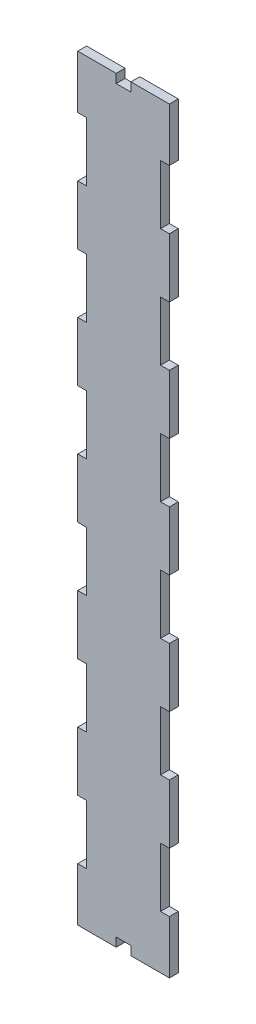
SolidWorks part; units mm, degrees
ref_plane "Front Plane" through (0, 0, 0) normal (0, 0, 1) x (1, 0, 0)
ref_plane "Top Plane" through (0, 0, 0) normal (0, 1, 0) x (1, 0, 0)
ref_plane "Right Plane" through (0, 0, 0) normal (1, 0, 0) x (0, 0, -1)
sketch "Эскиз2" plane through (0, 0, 0) normal (0, 0, 1) x (1, 0, 0)
  line L0 (-118.1292, 271.6721) -> (-110.4161, 271.6721)
  line L1 (-110.4161, 271.6721) -> (-110.4161, 276.0661)
  line L2 (-110.4161, 276.0661) -> (-86.722, 276.0661)
  line L3 (-86.722, 276.0661) -> (-86.722, 271.6721)
  line L4 (-86.722, 271.6721) -> (-64.5567, 271.6721)
  line L5 (-64.5567, 271.6721) -> (-64.5567, 276.0661)
  line L6 (-64.5567, 276.0661) -> (-40.8626, 276.0661)
  line L7 (-40.8626, 276.0661) -> (-40.8626, 271.6721)
  line L8 (-40.8626, 271.6721) -> (-10.2897, 271.6721)
  line L9 (-10.2897, 271.6721) -> (-10.2897, 248.237)
  line L10 (-10.2897, 248.237) -> (-4.5573, 248.237)
  line L11 (-4.5573, 248.237) -> (-4.5573, 230.0748)
  line L12 (-4.5573, 230.0748) -> (-10.2897, 230.0748)
  line L13 (-10.2897, 230.0748) -> (-10.2897, 213.0843)
  line L14 (-10.2897, 213.0843) -> (-4.5573, 213.0843)
  line L15 (-4.5573, 213.0843) -> (-4.5573, 194.9221)
  line L16 (-4.5573, 194.9221) -> (-10.2897, 194.9221)
  line L17 (-10.2897, 194.9221) -> (-10.2897, 177.9317)
  line L18 (-10.2897, 177.9317) -> (-4.5573, 177.9317)
  line L19 (-4.5573, 177.9317) -> (-4.5573, 159.7695)
  line L20 (-4.5573, 159.7695) -> (-10.2897, 159.7695)
  line L21 (-10.2897, 159.7695) -> (-10.2897, 142.7791)
  line L22 (-10.2897, 142.7791) -> (-4.5573, 142.7791)
  line L23 (-4.5573, 142.7791) -> (-4.5573, 124.6169)
  line L24 (-4.5573, 124.6169) -> (-10.2897, 124.6169)
  line L25 (-10.2897, 124.6169) -> (-10.2897, 107.6264)
  line L26 (-10.2897, 107.6264) -> (-4.5573, 107.6264)
  line L27 (-4.5573, 107.6264) -> (-4.5573, 89.4642)
  line L28 (-4.5573, 89.4642) -> (-10.2897, 89.4642)
  line L29 (-10.2897, 89.4642) -> (-10.2897, 72.4738)
  line L30 (-10.2897, 72.4738) -> (-4.5573, 72.4738)
  line L31 (-4.5573, 72.4738) -> (-4.5573, 54.3116)
  line L32 (-4.5573, 54.3116) -> (-10.2897, 54.3116)
  line L33 (-10.2897, 21.59) -> (-41.4508, 21.59)
  line L34 (-41.4508, 21.59) -> (-41.4508, 17.1959)
  line L35 (-41.4508, 17.1959) -> (-65.1449, 17.1959)
  line L36 (-65.1449, 17.1959) -> (-65.1449, 21.59)
  line L37 (-65.1449, 21.59) -> (-87.3102, 21.59)
  line L38 (-87.3102, 21.59) -> (-87.3102, 17.1959)
  line L39 (-87.3102, 17.1959) -> (-111.0043, 17.1959)
  line L40 (-111.0043, 17.1959) -> (-111.0043, 21.59)
  line L41 (-111.0043, 21.59) -> (-118.7174, 21.59)
  line L42 (-118.7174, 21.59) -> (-133.1696, 21.59)
  line L43 (-133.1696, 21.59) -> (-133.1696, 17.1959)
  line L44 (-133.1696, 17.1959) -> (-156.8637, 17.1959)
  line L45 (-156.8637, 17.1959) -> (-156.8637, 21.59)
  line L46 (-156.8637, 21.59) -> (-179.029, 21.59)
  line L47 (-179.029, 21.59) -> (-179.029, 17.1959)
  line L48 (-179.029, 17.1959) -> (-202.7231, 17.1959)
  line L49 (-202.7231, 17.1959) -> (-202.7231, 21.59)
  line L50 (-202.7231, 21.59) -> (-224.8885, 21.59)
  line L51 (-224.8885, 21.59) -> (-224.8885, 17.1959)
  line L52 (-224.8885, 17.1959) -> (-248.5825, 17.1959)
  line L53 (-248.5825, 17.1959) -> (-248.5825, 21.59)
  line L54 (-248.5825, 21.59) -> (-270.7479, 21.59)
  line L55 (-270.7479, 21.59) -> (-270.7479, 17.1959)
  line L56 (-270.7479, 17.1959) -> (-294.4419, 17.1959)
  line L57 (-294.4419, 17.1959) -> (-294.4419, 21.59)
  line L58 (-294.4419, 21.59) -> (-316.6073, 21.59)
  line L59 (-316.6073, 21.59) -> (-316.6073, 17.1959)
  line L60 (-316.6073, 17.1959) -> (-340.3013, 17.1959)
  line L61 (-340.3013, 17.1959) -> (-340.3013, 21.59)
  line L62 (-340.3013, 21.59) -> (-370.286, 21.59)
  line L63 (-370.286, 21.59) -> (-370.286, 54.3116)
  line L64 (-370.286, 54.3116) -> (-376.0185, 54.3116)
  line L65 (-376.0185, 54.3116) -> (-376.0185, 72.4738)
  line L66 (-376.0185, 72.4738) -> (-370.286, 72.4738)
  line L67 (-370.286, 72.4738) -> (-370.286, 89.4642)
  line L68 (-370.286, 89.4642) -> (-376.0185, 89.4642)
  line L69 (-376.0185, 89.4642) -> (-376.0185, 107.6264)
  line L70 (-376.0185, 107.6264) -> (-370.286, 107.6264)
  line L71 (-370.286, 107.6264) -> (-370.286, 124.6169)
  line L72 (-370.286, 124.6169) -> (-376.0185, 124.6169)
  line L73 (-376.0185, 124.6169) -> (-376.0185, 142.7791)
  line L74 (-376.0185, 142.7791) -> (-370.286, 142.7791)
  line L75 (-370.286, 142.7791) -> (-370.286, 159.7695)
  line L76 (-370.286, 159.7695) -> (-376.0185, 159.7695)
  line L77 (-376.0185, 159.7695) -> (-376.0185, 177.9317)
  line L78 (-376.0185, 177.9317) -> (-370.286, 177.9317)
  line L79 (-370.286, 177.9317) -> (-370.286, 194.9221)
  line L80 (-370.286, 194.9221) -> (-376.0185, 194.9221)
  line L81 (-376.0185, 194.9221) -> (-376.0185, 213.0843)
  line L82 (-376.0185, 213.0843) -> (-370.286, 213.0843)
  line L83 (-370.286, 213.0843) -> (-370.286, 230.0748)
  line L84 (-370.286, 230.0748) -> (-376.0185, 230.0748)
  line L85 (-376.0185, 230.0748) -> (-376.0185, 248.237)
  line L86 (-376.0185, 248.237) -> (-370.286, 248.237)
  line L87 (-370.286, 248.237) -> (-370.286, 271.6721)
  line L88 (-370.286, 271.6721) -> (-339.7131, 271.6721)
  line L89 (-339.7131, 271.6721) -> (-339.7131, 276.0661)
  line L90 (-339.7131, 276.0661) -> (-316.0191, 276.0661)
  line L91 (-316.0191, 276.0661) -> (-316.0191, 271.6721)
  line L92 (-316.0191, 271.6721) -> (-293.8537, 271.6721)
  line L93 (-293.8537, 271.6721) -> (-293.8537, 276.0661)
  line L94 (-293.8537, 276.0661) -> (-270.1597, 276.0661)
  line L95 (-270.1597, 276.0661) -> (-270.1597, 271.6721)
  line L96 (-270.1597, 271.6721) -> (-247.9943, 271.6721)
  line L97 (-247.9943, 271.6721) -> (-247.9943, 276.0661)
  line L98 (-247.9943, 276.0661) -> (-224.3003, 276.0661)
  line L99 (-224.3003, 276.0661) -> (-224.3003, 271.6721)
  line L100 (-224.3003, 271.6721) -> (-202.1349, 271.6721)
  line L101 (-202.1349, 271.6721) -> (-202.1349, 276.0661)
  line L102 (-202.1349, 276.0661) -> (-178.4408, 276.0661)
  line L103 (-178.4408, 276.0661) -> (-178.4408, 271.6721)
  line L104 (-178.4408, 271.6721) -> (-156.2755, 271.6721)
  line L105 (-156.2755, 271.6721) -> (-156.2755, 276.0661)
  line L106 (-156.2755, 276.0661) -> (-132.5814, 276.0661)
  line L107 (-132.5814, 276.0661) -> (-132.5814, 271.6721)
  line L108 (-132.5814, 271.6721) -> (-118.1292, 271.6721)
  line L109 (-373.2759, 10.3396) -> (-342.8312, 10.3396)
  line L110 (-342.8312, 10.3396) -> (-342.8312, 6.0284)
  line L111 (-342.8312, 6.0284) -> (-318.4281, 6.0284)
  line L112 (-318.4281, 6.0284) -> (-318.4281, 10.3396)
  line L113 (-318.4281, 10.3396) -> (-296.972, 10.3396)
  line L114 (-296.972, 10.3396) -> (-296.972, 6.0284)
  line L115 (-296.972, 6.0284) -> (-272.5865, 6.0284)
  line L116 (-272.5865, 6.0284) -> (-272.5865, 10.3396)
  line L117 (-272.5865, 10.3396) -> (-251.1875, 10.3396)
  line L118 (-251.1875, 10.3396) -> (-251.1875, 6.0284)
  line L119 (-251.1875, 6.0284) -> (-226.6927, 6.0284)
  line L120 (-226.6927, 6.0284) -> (-226.6927, 10.3396)
  line L121 (-226.6927, 10.3396) -> (-205.259, 10.3396)
  line L122 (-205.259, 10.3396) -> (-205.259, 6.0284)
  line L123 (-205.259, 6.0284) -> (-180.8925, 6.0284)
  line L124 (-180.8925, 6.0284) -> (-180.8925, 10.3396)
  line L125 (-180.8925, 10.3396) -> (-159.5195, 10.3396)
  line L126 (-159.5195, 10.3396) -> (-159.5195, 6.0284)
  line L127 (-159.5195, 6.0284) -> (-135.0267, 6.0284)
  line L128 (-135.0267, 6.0284) -> (-135.0267, 10.3396)
  line L129 (-135.0267, 10.3396) -> (-113.5788, 10.3396)
  line L130 (-113.5788, 10.3396) -> (-113.5788, 6.0284)
  line L131 (-113.5788, 6.0284) -> (-89.2114, 6.0284)
  line L132 (-89.2114, 6.0284) -> (-89.2114, 10.3396)
  line L133 (-89.2114, 10.3396) -> (-67.739, 10.3396)
  line L134 (-67.739, 10.3396) -> (-67.739, 6.0284)
  line L135 (-67.739, 6.0284) -> (-43.1804, 6.0284)
  line L136 (-43.1804, 6.0284) -> (-43.1804, 10.3396)
  line L137 (-43.1804, 10.3396) -> (-12.8557, 10.3396)
  line L138 (-12.8557, 10.3396) -> (-12.8557, -1.3472)
  line L139 (-12.8557, -1.3472) -> (-4.8129, -1.3472)
  line L140 (-4.8129, -1.3472) -> (-4.8194, -8.2165)
  line L141 (-4.8194, -8.2165) -> (-12.8557, -8.2165)
  line L142 (-12.8557, -8.2165) -> (-12.8557, -21.1423)
  line L143 (-12.8557, -21.1423) -> (-43.1804, -21.1423)
  line L144 (-43.1804, -21.1423) -> (-43.1804, -17.4156)
  line L145 (-43.1804, -17.4156) -> (-67.739, -17.4156)
  line L146 (-67.739, -17.4156) -> (-67.739, -21.1423)
  line L147 (-67.739, -21.1423) -> (-89.2114, -21.1423)
  line L148 (-89.2114, -21.1423) -> (-89.2114, -17.4156)
  line L149 (-89.2114, -17.4156) -> (-113.5788, -17.4156)
  line L150 (-113.5788, -17.4156) -> (-113.5788, -21.1423)
  line L151 (-113.5788, -21.1423) -> (-135.0267, -21.1423)
  line L152 (-135.0267, -21.1423) -> (-135.0267, -17.4156)
  line L153 (-135.0267, -17.4156) -> (-159.5195, -17.4156)
  line L154 (-159.5195, -17.4156) -> (-159.5195, -21.1423)
  line L155 (-159.5195, -21.1423) -> (-180.8925, -21.1423)
  line L156 (-180.8925, -21.1423) -> (-180.8931, -17.4156)
  line L157 (-180.8931, -17.4156) -> (-205.259, -17.4156)
  line L158 (-205.259, -17.4156) -> (-205.259, -21.1423)
  line L159 (-205.259, -21.1423) -> (-226.6927, -21.1423)
  line L160 (-226.6927, -21.1423) -> (-226.6927, -17.4156)
  line L161 (-226.6927, -17.4156) -> (-251.1875, -17.4156)
  line L162 (-251.1875, -17.4156) -> (-251.1875, -21.1423)
  line L163 (-251.1875, -21.1423) -> (-272.5865, -21.1423)
  line L164 (-272.5865, -21.1423) -> (-272.5865, -17.4156)
  line L165 (-272.5865, -17.4156) -> (-296.972, -17.4156)
  line L166 (-296.972, -17.4156) -> (-296.972, -21.1423)
  line L167 (-296.972, -21.1423) -> (-318.4281, -21.1423)
  line L168 (-318.4281, -21.1423) -> (-318.4281, -17.4156)
  line L169 (-318.4281, -17.4156) -> (-342.8312, -17.4156)
  line L170 (-342.8312, -17.4156) -> (-342.8312, -21.1423)
  line L171 (-342.8312, -21.1423) -> (-373.2759, -21.1423)
  line L172 (-373.2759, -21.1423) -> (-373.2759, -8.4164)
  line L173 (-373.2759, -8.4164) -> (-379.9791, -8.4164)
  line L174 (-379.9791, -8.4164) -> (-379.9791, -1.5471)
  line L175 (-379.9791, -1.5471) -> (-373.2759, -1.5471)
  line L176 (-373.2759, -1.5471) -> (-373.2759, 10.3396)
  line L177 (-309.7012, -8.7624) -> (-309.7012, -1.506)
  line L178 (-309.7012, -1.506) -> (-306.8626, -1.506)
  line L179 (-306.8626, -1.506) -> (-306.8626, -8.7624)
  line L180 (-306.8626, -8.7624) -> (-309.7012, -8.7624)
  line L181 (-339.711, -8.7225) -> (-339.711, -1.4885)
  line L182 (-339.711, -1.4885) -> (-336.8724, -1.4885)
  line L183 (-336.8724, -1.4885) -> (-336.8724, -8.7225)
  line L184 (-336.8724, -8.7225) -> (-339.711, -8.7225)
  line L185 (-279.6954, -8.7125) -> (-279.6954, -1.4785)
  line L186 (-279.6954, -1.4785) -> (-276.8568, -1.4785)
  line L187 (-276.8568, -1.4785) -> (-276.8568, -8.7125)
  line L188 (-276.8568, -8.7125) -> (-279.6954, -8.7125)
  line L189 (-249.6976, -8.7086) -> (-249.6976, -1.496)
  line L190 (-249.6976, -1.496) -> (-246.859, -1.496)
  line L191 (-246.859, -1.496) -> (-246.859, -8.7086)
  line L192 (-246.859, -8.7086) -> (-249.6976, -8.7086)
  line L193 (-189.6776, -8.5964) -> (-189.6776, -1.4885)
  line L194 (-189.6776, -1.4885) -> (-186.839, -1.4885)
  line L195 (-186.839, -1.4885) -> (-186.839, -8.5964)
  line L196 (-186.839, -8.5964) -> (-189.6776, -8.5964)
  line L197 (-216.8557, -1.4884) -> (-216.8557, -5.6266)
  line L198 (-216.8557, -5.6266) -> (-216.8557, -8.6615)
  line L199 (-216.8557, -8.6615) -> (-219.6943, -8.6615)
  line L200 (-219.6943, -8.6615) -> (-219.6943, -1.4884)
  line L201 (-219.6943, -1.4884) -> (-216.8557, -1.4884)
  line L202 (-159.6718, -8.4591) -> (-159.6718, -1.4885)
  line L203 (-159.6718, -1.4885) -> (-156.8332, -1.4885)
  line L204 (-156.8332, -1.4885) -> (-156.8332, -8.4591)
  line L205 (-156.8332, -8.4591) -> (-159.6718, -8.4591)
  line L206 (-126.0755, -8.4753) -> (-126.0755, -1.4794)
  line L207 (-126.0755, -1.4794) -> (-123.2266, -1.4794)
  line L208 (-123.2266, -1.4794) -> (-123.2266, -8.4753)
  line L209 (-123.2266, -8.4753) -> (-126.0755, -8.4753)
  line L210 (32.0426, 264.3465) -> (32.0426, 233.4466)
  line L211 (32.0426, 233.4466) -> (26.1557, 233.4466)
  line L212 (26.1557, 233.4466) -> (26.1557, 214.8844)
  line L213 (26.1557, 214.8844) -> (32.0426, 214.8844)
  line L214 (32.0426, 214.8844) -> (32.0426, 198.2939)
  line L215 (32.0426, 198.2939) -> (26.1557, 198.2939)
  line L216 (26.1557, 198.2939) -> (26.1557, 179.5405)
  line L217 (26.1557, 179.5405) -> (32.0426, 179.5405)
  line L218 (32.0426, 179.5405) -> (32.0426, 163.1413)
  line L219 (32.0426, 163.1413) -> (26.1557, 163.1413)
  line L220 (26.1557, 163.1413) -> (26.1557, 144.7791)
  line L221 (26.1557, 144.7791) -> (32.0426, 144.7791)
  line L222 (32.0426, 144.7791) -> (32.0426, 127.9887)
  line L223 (32.0426, 127.9887) -> (26.1557, 127.9887)
  line L224 (26.1557, 127.9887) -> (26.1557, 109.4265)
  line L225 (26.1557, 109.4265) -> (32.0426, 109.4265)
  line L226 (32.0426, 109.4265) -> (32.0426, 92.836)
  line L227 (32.0426, 92.836) -> (26.1557, 92.836)
  line L228 (26.1557, 92.836) -> (26.1557, 74.4738)
  line L229 (26.1557, 74.4738) -> (32.0426, 74.4738)
  line L230 (32.0426, 74.4738) -> (32.0426, 57.4834)
  line L231 (32.0426, 57.4834) -> (26.1557, 57.4834)
  line L232 (26.1557, 57.4834) -> (26.1557, 39.3212)
  line L233 (26.1557, 39.3212) -> (32.0426, 39.3212)
  line L234 (32.0426, 39.3212) -> (32.0426, 29.9952)
  line L235 (32.0426, 29.9952) -> (32.0426, -0.6964)
  line L236 (32.0426, -0.6964) -> (20.0028, -0.6964)
  line L237 (20.0028, -0.6964) -> (20.0028, 6.7202)
  line L238 (20.0028, 6.7202) -> (12.704, 6.7202)
  line L239 (12.704, 6.7202) -> (12.704, -0.6964)
  line L240 (12.704, -0.6964) -> (-0.0144, -0.6964)
  line L241 (-0.0144, 39.3212) -> (6.3507, 39.3212)
  line L242 (6.3507, 39.3212) -> (6.3507, 57.4834)
  line L243 (6.3507, 57.4834) -> (-0.0144, 57.4834)
  line L244 (-0.0144, 57.4834) -> (-0.0144, 74.4738)
  line L245 (-0.0144, 74.4738) -> (6.3507, 74.4738)
  line L246 (6.3507, 74.4738) -> (6.3507, 92.836)
  line L247 (6.3507, 92.836) -> (-0.0144, 92.836)
  line L248 (-0.0144, 92.836) -> (-0.0144, 109.4265)
  line L249 (-0.0144, 109.4265) -> (6.3507, 109.4265)
  line L250 (6.3507, 109.4265) -> (6.3507, 127.9887)
  line L251 (6.3507, 127.9887) -> (-0.0144, 127.9887)
  line L252 (-0.0144, 127.9887) -> (-0.0144, 144.7791)
  line L253 (-0.0144, 144.7791) -> (6.3507, 144.7791)
  line L254 (6.3507, 144.7791) -> (6.3507, 163.1413)
  line L255 (6.3507, 163.1413) -> (-0.0144, 163.1413)
  line L256 (-0.0144, 163.1413) -> (-0.0144, 179.5405)
  line L257 (-0.0144, 179.5405) -> (6.3507, 179.5405)
  line L258 (6.3507, 179.5405) -> (6.3507, 198.2939)
  line L259 (6.3507, 198.2939) -> (-0.0144, 198.2939)
  line L260 (-0.0144, 198.2939) -> (-0.0144, 214.8844)
  line L261 (-0.0144, 214.8844) -> (6.3507, 214.8844)
  line L262 (6.3507, 214.8844) -> (6.3507, 233.4466)
  line L263 (6.3507, 233.4466) -> (-0.0144, 233.4466)
  line L264 (-0.0144, 233.4466) -> (-0.0144, 264.3465)
  line L265 (-0.0144, 264.3465) -> (13.0137, 264.3465)
  line L266 (13.0137, 264.3465) -> (13.0137, 256.7736)
  line L267 (13.0137, 256.7736) -> (19.9331, 256.7736)
  line L268 (19.9331, 256.7736) -> (19.9331, 264.3465)
  line L269 (19.9331, 264.3465) -> (32.0426, 264.3465)
  line L270 (12.6691, 193.1597) -> (19.9255, 193.1597)
  line L271 (19.9255, 193.1597) -> (19.9255, 190.3211)
  line L272 (19.9255, 190.3211) -> (12.6691, 190.3211)
  line L273 (12.6691, 190.3211) -> (12.6691, 193.1597)
  line L274 (12.709, 223.1695) -> (19.943, 223.1695)
  line L275 (19.943, 223.1695) -> (19.943, 220.3309)
  line L276 (19.943, 220.3309) -> (12.709, 220.3309)
  line L277 (12.709, 220.3309) -> (12.709, 223.1695)
  line L278 (12.719, 163.1539) -> (19.953, 163.1539)
  line L279 (19.953, 163.1539) -> (19.953, 160.3153)
  line L280 (19.953, 160.3153) -> (12.719, 160.3153)
  line L281 (12.719, 160.3153) -> (12.719, 163.1539)
  line L282 (12.7229, 133.1561) -> (19.9355, 133.1561)
  line L283 (19.9355, 133.1561) -> (19.9355, 130.3175)
  line L284 (19.9355, 130.3175) -> (12.7229, 130.3175)
  line L285 (12.7229, 130.3175) -> (12.7229, 133.1561)
  line L286 (12.8351, 73.1361) -> (19.943, 73.1361)
  line L287 (19.943, 73.1361) -> (19.943, 70.2975)
  line L288 (19.943, 70.2975) -> (12.8351, 70.2975)
  line L289 (12.8351, 70.2975) -> (12.8351, 73.1361)
  line L290 (19.9431, 100.3142) -> (15.8049, 100.3142)
  line L291 (15.8049, 100.3142) -> (12.77, 100.3142)
  line L292 (12.77, 100.3142) -> (12.77, 103.1528)
  line L293 (12.77, 103.1528) -> (19.9431, 103.1528)
  line L294 (19.9431, 103.1528) -> (19.9431, 100.3142)
  line L295 (12.9724, 43.1303) -> (19.943, 43.1303)
  line L296 (19.943, 43.1303) -> (19.943, 40.2917)
  line L297 (19.943, 40.2917) -> (12.9724, 40.2917)
  line L298 (12.9724, 40.2917) -> (12.9724, 43.1303)
  spline S0 degree 3 poles (-10.2897, 54.3116) (-10.2897, 27.8097) (-10.2897, 51.5005) (-10.2897, 21.59) knots 0.3 0.3 0.3 0.3 0.309091 0.309091 0.309091 0.309091
  spline S1 degree 3 poles (-0.0144, -0.6964) (-0.0144, 12.6428) (-0.0144, 25.982) (-0.0144, 39.3212) knots 0.508197 0.508197 0.508197 0.508197 0.52459 0.52459 0.52459 0.52459
sketch "Sketch2" plane through (0, 0, 0) normal (0, 0, 1) x (1, 0, 0)
  line L0 (12.5, 250) -> (12.5, 0) construction
  line L1 (10, 250) -> (15, 250)
  line L2 (0, 235) -> (0, 215)
  line L3 (10, 0) -> (15, 0)
  line L4 (25, 235) -> (25, 215)
  line L7 (0, 253) -> (10, 253)
  line L8 (10, 250) -> (10, 253)
  line L9 (15, 250) -> (15, 253)
  line L12 (15, 253) -> (25, 253)
  line L14 (25, 253) -> (28, 253)
  line L16 (25, 235) -> (28, 235)
  line L17 (28, 253) -> (28, 235)
  line L18 (25, 215) -> (28, 215)
  line L20 (25, 195) -> (28, 195)
  line L21 (28, 215) -> (28, 195)
  line L22 (25, 175) -> (28, 175)
  line L23 (28, 175) -> (28, 155)
  line L24 (25, 155) -> (28, 155)
  line L26 (25, 135) -> (28, 135)
  line L27 (28, 135) -> (28, 115)
  line L28 (25, 115) -> (28, 115)
  line L30 (25, 95) -> (28, 95)
  line L31 (28, 95) -> (28, 75)
  line L32 (25, 75) -> (28, 75)
  line L34 (25, 55) -> (28, 55)
  line L35 (28, 55) -> (28, 35)
  line L36 (25, 35) -> (28, 35)
  line L37 (0, 125) -> (53.8422, 125) construction
  line L38 (25, 15) -> (28, 15)
  line L39 (28, -3) -> (28, 15)
  line L40 (25, -3) -> (28, -3)
  line L42 (0, -3) -> (10, -3)
  line L43 (10, 0) -> (10, -3)
  line L47 (15, -3) -> (25, -3)
  line L48 (15, 0) -> (15, -3)
  line L49 (25, 35) -> (25, 15)
  line L50 (0, -3) -> (-3, -3)
  line L51 (-3, -3) -> (-3, 15)
  line L52 (0, 15) -> (-3, 15)
  line L54 (0, 55) -> (-3, 55)
  line L55 (-3, 55) -> (-3, 35)
  line L56 (0, 35) -> (-3, 35)
  line L58 (0, 95) -> (-3, 95)
  line L59 (-3, 95) -> (-3, 75)
  line L60 (0, 75) -> (-3, 75)
  line L62 (0, 135) -> (-3, 135)
  line L63 (-3, 135) -> (-3, 115)
  line L64 (0, 115) -> (-3, 115)
  line L66 (0, 175) -> (-3, 175)
  line L67 (-3, 175) -> (-3, 155)
  line L68 (0, 155) -> (-3, 155)
  line L70 (0, 195) -> (-3, 195)
  line L71 (-3, 215) -> (-3, 195)
  line L72 (0, 215) -> (-3, 215)
  line L74 (0, 235) -> (-3, 235)
  line L75 (-3, 253) -> (-3, 235)
  line L76 (0, 253) -> (-3, 253)
  line L78 (25, 250) -> (25, 253) [skipped]
  line L79 (0, 195) -> (0, 175)
  line L80 (25, 195) -> (25, 175)
  line L81 (25, 155) -> (25, 135)
  line L82 (0, 155) -> (0, 135)
  line L83 (0, 115) -> (0, 95)
  line L84 (0, 35) -> (0, 15)
  line L85 (0, 75) -> (0, 55)
  line L86 (25, 75) -> (25, 55)
  line L87 (25, 115) -> (25, 95)
  point P10 (25, 235)
  point P102 (12.5, 223)
  dimension "D2" = 18
  dimension "D3" = 25
  dimension "D4" = 10
  dimension "D6" = 3
  dimension "D7" = 3
  dimension "D8" = 3
  dimension "D9" = 20
  dimension "D10" = 20
  dimension "D12" = 20
  dimension "D13" = 3
  dimension "D14" = 250
  dimension "D5" = 2
  dimension "D11" = 5
extrude "Boss-Extrude3" add sketch "Sketch2" along normal blind 3
